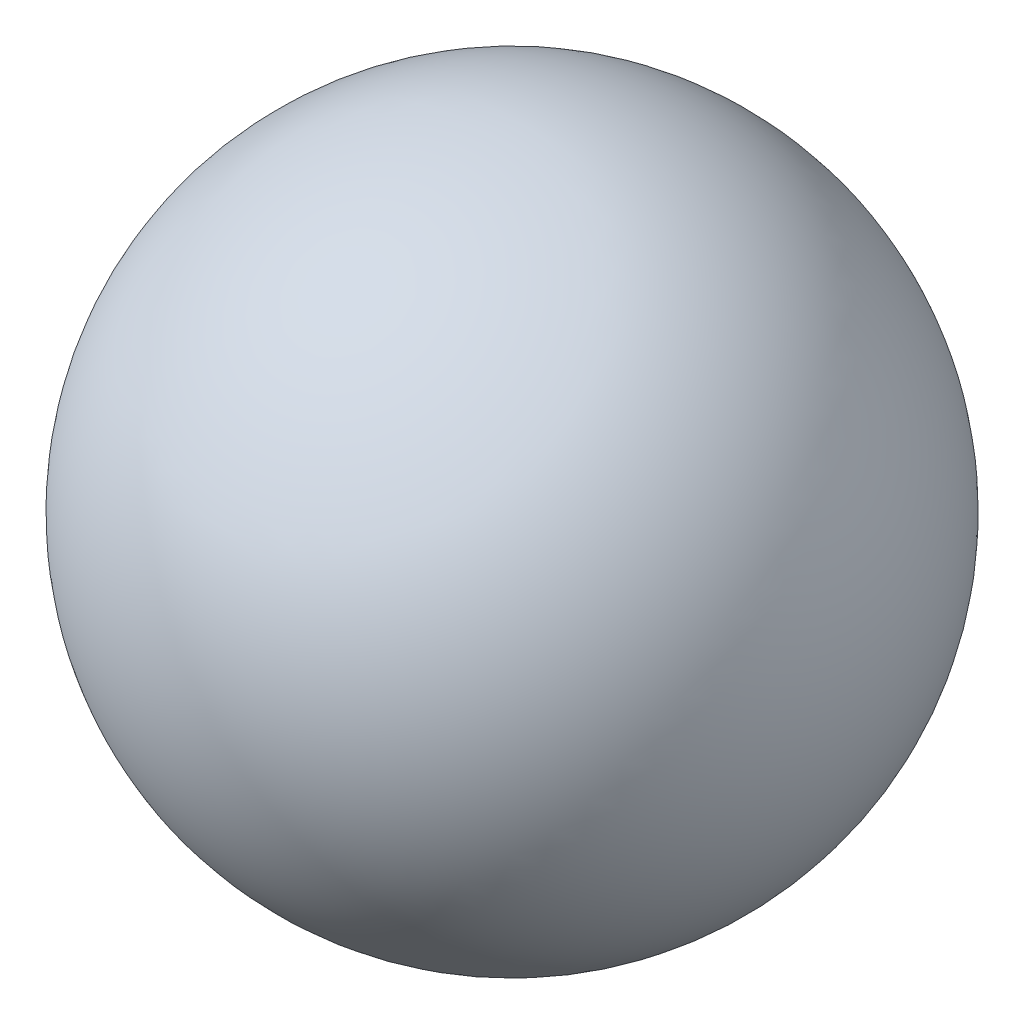
SolidWorks part; units mm, degrees
ref_plane "Front Plane" through (0, 0, 0) normal (0, 0, 1) x (1, 0, 0)
ref_plane "Top Plane" through (0, 0, 0) normal (0, 1, 0) x (1, 0, 0)
ref_plane "Right Plane" through (0, 0, 0) normal (1, 0, 0) x (0, 0, -1)
sketch "Sketch1" plane through (0, 0, 0) normal (0, 1, 0) x (1, 0, 0)
  line L0 (0, -176.9996) -> (0, 172.7916) construction
  line L1 (0, 127) -> (0, -127)
  arc A0 (0, -127) -> (0, 127) centre (0, 0) ccw
  dimension "D1" = 254
revolve "Revolve6" add sketch "Sketch1" angle 360 about L0
